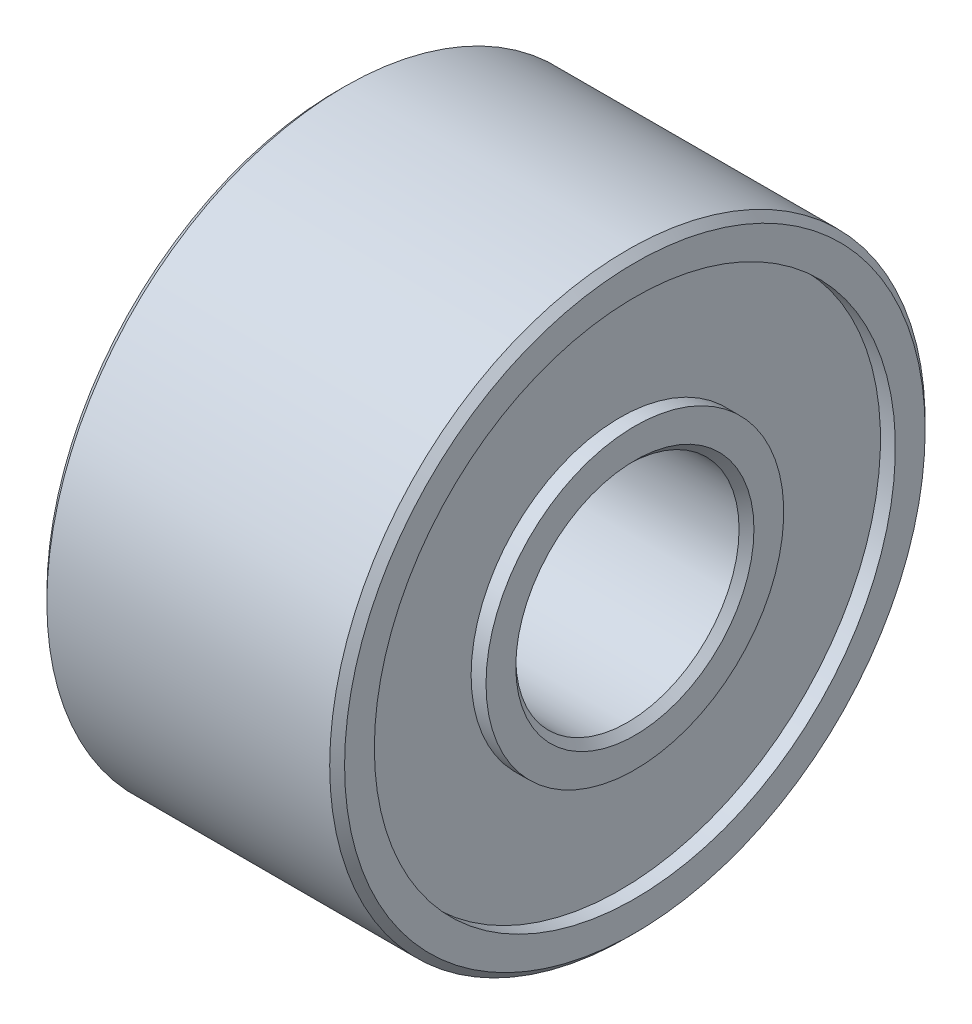
SolidWorks part; units mm, degrees
ref_plane "前视基准面" through (0, 0, 0) normal (0, 0, 1) x (1, 0, 0)
ref_plane "上视基准面" through (0, 0, 0) normal (0, 1, 0) x (1, 0, 0)
ref_plane "右视基准面" through (0, 0, 0) normal (1, 0, 0) x (0, 0, -1)
sketch "草图1" plane through (0, 0, 0) normal (0, 0, 1) x (1, 0, 0)
  line L0 (-16.4449, 0) -> (12.3385, 0) construction
  line L1 (0, 12.3772) -> (0, 3.5) construction
  line L2 (0, 1.5) -> (0, 2)
  line L3 (0, 4) -> (-4, 4)
  line L4 (-4, 4) -> (-4, 3.5)
  line L5 (-4, 1.5) -> (0, 1.5)
  line L6 (0, 3.5) -> (-0.2, 3.5)
  line L7 (-0.2, 3.5) -> (-0.2, 2)
  line L8 (-0.2, 2) -> (0, 2)
  line L9 (-2, 4.2549) -> (-2, 1.2462) construction
  line L10 (-3.8, 3.5) -> (-4, 3.5)
  line L11 (-3.8, 3.5) -> (-3.8, 2)
  line L12 (0, 2) -> (0, -9.743) construction
  line L13 (0, 3.5) -> (0, 4)
  line L15 (-3.8, 2) -> (-4, 2)
  line L16 (-4, 2) -> (-4, 1.5)
  dimension "D1" = 3
  dimension "D2" = 8
  dimension "D3" = 4
  dimension "D4" = 0.5
  dimension "D5" = 0.5
  dimension "D6" = 0.2
  dimension "D7" = 2
revolve "旋转1" add sketch "草图1" angle 360 about L0
chamfer "倒角1" distance 0.1 angle 45 4 edges at (-4, 0, 1.5) (0, 0, 1.5) (-4, 0, 4) (0, 0, 4)
